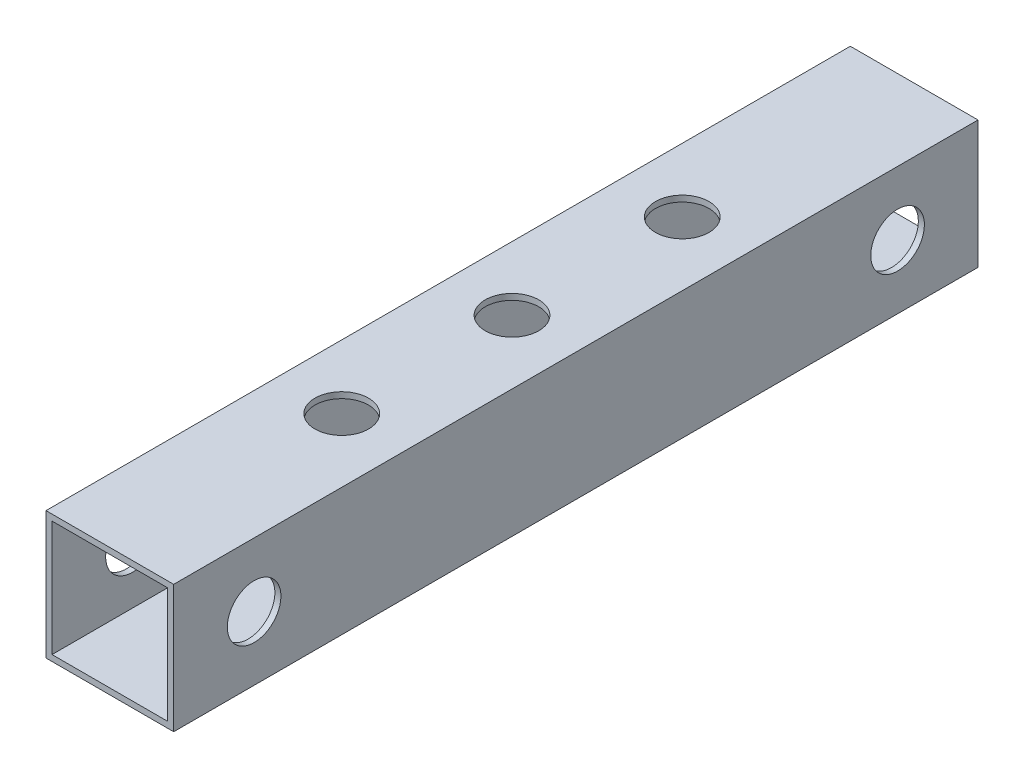
SolidWorks part; units mm, degrees
material "6061-T4 (SS)"
ref_plane "Front Plane" through (0, 0, 0) normal (0, 0, 1) x (1, 0, 0)
ref_plane "Top Plane" through (0, 0, 0) normal (0, 1, 0) x (1, 0, 0)
ref_plane "Right Plane" through (0, 0, 0) normal (1, 0, 0) x (0, 0, -1)
sketch "Sketch1" plane through (0, 0, 0) normal (0, 0, 1) x (1, 0, 0)
  line L1 (-9.525, 9.525) -> (9.525, 9.525)
  line L2 (-9.525, 9.525) -> (-9.525, -9.525)
  line L3 (-9.525, -9.525) -> (9.525, -9.525)
  line L4 (9.525, 9.525) -> (9.525, -9.525)
  line L5 (-9.525, 9.525) -> (9.525, -9.525) construction
  line L6 (-9.525, -9.525) -> (9.525, 9.525) construction
  point P0 (0, 0)
  dimension "D1" = 19.05
  dimension "D2" = 19.05
extrude "Extrude-Thin1" add sketch "Sketch1" along normal mid plane 120 thin
sketch "Sketch2" plane through (9.525, 0, 0) normal (1, 0, 0) x (0, 0, -1)
  line L0 (-60, -9.525) -> (-60, 9.525) construction
  line L1 (60, -9.525) -> (60, 9.525) construction
  line L2 (-48, 0) -> (48, 0) construction
  line L3 (0, 9.525) -> (0, -9.525) construction
  line L4 (-60, 9.525) -> (60, 9.525) construction
  line L5 (-60, -9.525) -> (60, -9.525) construction
  circle A0 centre (-48, 0) radius 4
  circle A1 centre (48, 0) radius 4
  dimension "D1" = 8
  dimension "D3" = 8
  dimension "D2" = 12
  dimension "D4" = 12
extrude "Cut-Extrude1" cut sketch "Sketch2" against normal through all
sketch "Sketch3" plane through (0, 9.525, 0) normal (0, 1, 0) x (1, 0, 0)
  line L0 (0, 25.4) -> (0, -25.4) construction
  circle A0 centre (0, -25.4) radius 4
  circle A1 centre (0, 25.4) radius 4
  circle A2 centre (0, 0) radius 4
  dimension "D1" = 8
  dimension "D2" = 50.8
extrude "Cut-Extrude2" cut sketch "Sketch3" against normal through all
move or copy body "Body-Move/Copy1" [suppressed] bodies to move or copy 103
